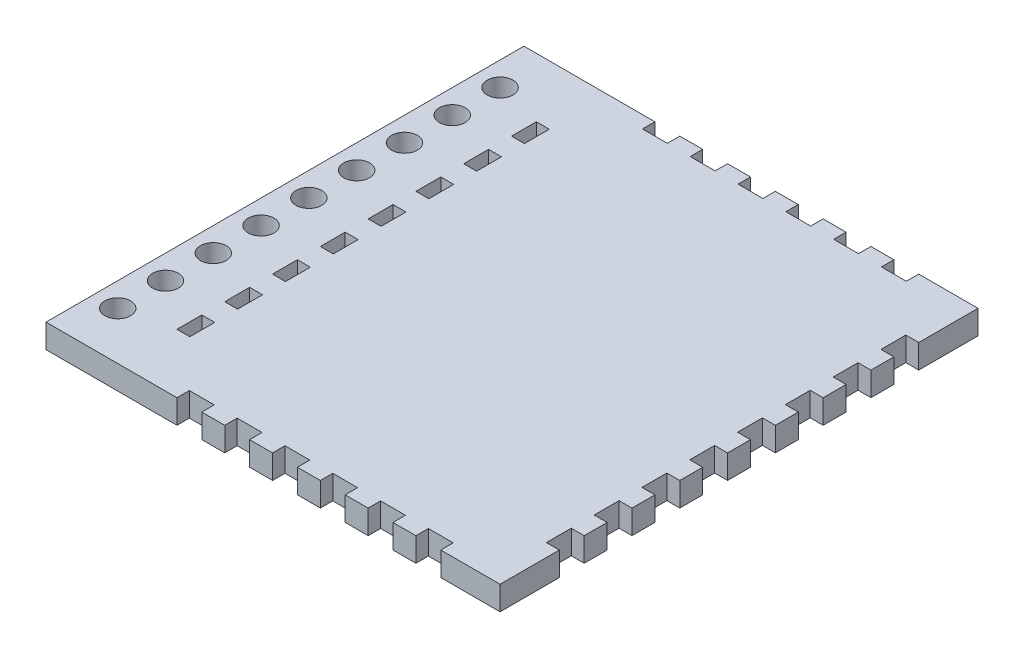
SolidWorks part; units mm, degrees
ref_plane "Front Plane" through (0, 0, 0) normal (0, 0, 1) x (1, 0, 0)
ref_plane "Top Plane" through (0, 0, 0) normal (0, 1, 0) x (1, 0, 0)
ref_plane "Right Plane" through (0, 0, 0) normal (1, 0, 0) x (0, 0, -1)
sketch "Sketch1" plane through (0, 0, 0) normal (0, 1, 0) x (1, 0, 0)
  line L1 (-50.8, -63.5) -> (50.8, -63.5)
  line L2 (-50.8, -63.5) -> (-50.8, 63.5)
  line L3 (-50.8, 63.5) -> (50.8, 63.5)
  line L4 (50.8, -63.5) -> (50.8, 63.5)
  line L5 (-50.8, -63.5) -> (50.8, 63.5) construction
  line L6 (-50.8, 63.5) -> (50.8, -63.5) construction
  line L11 (-41.275, -53.975) -> (41.275, 53.975) construction
  line L12 (-41.275, 53.975) -> (41.275, -53.975) construction
  point P0 (0, 0)
  point P5 (0, 0)
  dimension "D1" = 101.6
  dimension "D2" = 127
extrude "Boss-Extrude1" add sketch "Sketch1" along normal blind 6.35
sketch "Sketch2" plane through (0, 6.35, 0) normal (0, 1, 0) x (1, 0, 0)
  line L0 (-50.8, -63.5) -> (50.8, -63.5) construction
  line L1 (-35.052, -63.5) -> (-28.448, -63.5)
  line L2 (-35.052, -63.5) -> (-35.052, -60.198)
  line L3 (-35.052, -60.198) -> (-28.448, -60.198)
  line L4 (-28.448, -63.5) -> (-28.448, -60.198)
  line L5 (-22.352, -63.5) -> (-22.352, -60.198)
  line L6 (-22.352, -63.5) -> (-15.748, -63.5)
  line L7 (-15.748, -63.5) -> (-15.748, -60.198)
  line L8 (-22.352, -60.198) -> (-15.748, -60.198)
  line L9 (-9.652, -63.5) -> (-9.652, -60.198)
  line L10 (-9.652, -63.5) -> (-3.048, -63.5)
  line L11 (-3.048, -63.5) -> (-3.048, -60.198)
  line L12 (-9.652, -60.198) -> (-3.048, -60.198)
  line L13 (3.048, -63.5) -> (3.048, -60.198)
  line L14 (3.048, -63.5) -> (9.652, -63.5)
  line L15 (9.652, -63.5) -> (9.652, -60.198)
  line L16 (3.048, -60.198) -> (9.652, -60.198)
  line L17 (15.748, -63.5) -> (15.748, -60.198)
  line L18 (15.748, -63.5) -> (22.352, -63.5)
  line L19 (22.352, -63.5) -> (22.352, -60.198)
  line L20 (15.748, -60.198) -> (22.352, -60.198)
  line L21 (28.448, -63.5) -> (28.448, -60.198)
  line L22 (28.448, -63.5) -> (35.052, -63.5)
  line L23 (35.052, -63.5) -> (35.052, -60.198)
  line L24 (28.448, -60.198) -> (35.052, -60.198)
  line L25 (0, 0) -> (9.652, 0) construction
  line L26 (28.448, 60.198) -> (35.052, 60.198)
  line L27 (35.052, 63.5) -> (35.052, 60.198)
  line L28 (28.448, 63.5) -> (35.052, 63.5)
  line L29 (28.448, 63.5) -> (28.448, 60.198)
  line L30 (15.748, 60.198) -> (22.352, 60.198)
  line L31 (22.352, 63.5) -> (22.352, 60.198)
  line L32 (15.748, 63.5) -> (22.352, 63.5)
  line L33 (15.748, 63.5) -> (15.748, 60.198)
  line L34 (3.048, 60.198) -> (9.652, 60.198)
  line L35 (9.652, 63.5) -> (9.652, 60.198)
  line L36 (3.048, 63.5) -> (9.652, 63.5)
  line L37 (3.048, 63.5) -> (3.048, 60.198)
  line L38 (-9.652, 60.198) -> (-3.048, 60.198)
  line L39 (-3.048, 63.5) -> (-3.048, 60.198)
  line L40 (-9.652, 63.5) -> (-3.048, 63.5)
  line L41 (-9.652, 63.5) -> (-9.652, 60.198)
  line L42 (-22.352, 60.198) -> (-15.748, 60.198)
  line L43 (-15.748, 63.5) -> (-15.748, 60.198)
  line L44 (-22.352, 63.5) -> (-15.748, 63.5)
  line L45 (-22.352, 63.5) -> (-22.352, 60.198)
  line L46 (-28.448, 63.5) -> (-28.448, 60.198)
  line L47 (-35.052, 60.198) -> (-28.448, 60.198)
  line L48 (-35.052, 63.5) -> (-35.052, 60.198)
  line L49 (-35.052, 63.5) -> (-28.448, 63.5)
  line L50 (-50.8, 63.5) -> (-50.8, -63.5) construction
  line L51 (-50.8, 28.448) -> (-47.371, 28.448)
  line L52 (-50.8, 28.448) -> (-50.8, 35.052)
  line L53 (-50.8, 35.052) -> (-47.371, 35.052)
  line L54 (-47.371, 28.448) -> (-47.371, 35.052)
  line L55 (50.8, 63.5) -> (-50.8, 63.5) construction
  line L56 (-50.8, 15.748) -> (-47.371, 15.748)
  line L57 (-50.8, 15.748) -> (-50.8, 22.352)
  line L58 (-50.8, 22.352) -> (-47.371, 22.352)
  line L59 (-47.371, 15.748) -> (-47.371, 22.352)
  line L60 (-50.8, 3.048) -> (-47.371, 3.048)
  line L61 (-50.8, 3.048) -> (-50.8, 9.652)
  line L62 (-50.8, 9.652) -> (-47.371, 9.652)
  line L63 (-47.371, 3.048) -> (-47.371, 9.652)
  line L64 (-50.8, -9.652) -> (-47.371, -9.652)
  line L65 (-50.8, -9.652) -> (-50.8, -3.048)
  line L66 (-50.8, -3.048) -> (-47.371, -3.048)
  line L67 (-47.371, -9.652) -> (-47.371, -3.048)
  line L68 (-50.8, -22.352) -> (-47.371, -22.352)
  line L69 (-50.8, -22.352) -> (-50.8, -15.748)
  line L70 (-50.8, -15.748) -> (-47.371, -15.748)
  line L71 (-47.371, -22.352) -> (-47.371, -15.748)
  line L72 (-50.8, -35.052) -> (-47.371, -35.052)
  line L73 (-50.8, -35.052) -> (-50.8, -28.448)
  line L74 (-50.8, -28.448) -> (-47.371, -28.448)
  line L75 (-47.371, -35.052) -> (-47.371, -28.448)
  line L84 (0, 0) -> (0, 15.748) construction
  line L93 (47.371, -35.052) -> (47.371, -28.448)
  line L94 (50.8, -28.448) -> (47.371, -28.448)
  line L95 (50.8, -35.052) -> (50.8, -28.448)
  line L96 (50.8, -35.052) -> (47.371, -35.052)
  line L97 (47.371, -22.352) -> (47.371, -15.748)
  line L98 (50.8, -15.748) -> (47.371, -15.748)
  line L99 (50.8, -22.352) -> (50.8, -15.748)
  line L100 (50.8, -22.352) -> (47.371, -22.352)
  line L101 (47.371, -9.652) -> (47.371, -3.048)
  line L102 (50.8, -3.048) -> (47.371, -3.048)
  line L103 (50.8, -9.652) -> (50.8, -3.048)
  line L104 (50.8, -9.652) -> (47.371, -9.652)
  line L105 (47.371, 3.048) -> (47.371, 9.652)
  line L106 (50.8, 9.652) -> (47.371, 9.652)
  line L107 (50.8, 3.048) -> (50.8, 9.652)
  line L108 (50.8, 3.048) -> (47.371, 3.048)
  line L109 (47.371, 15.748) -> (47.371, 22.352)
  line L110 (50.8, 22.352) -> (47.371, 22.352)
  line L111 (50.8, 15.748) -> (50.8, 22.352)
  line L112 (50.8, 15.748) -> (47.371, 15.748)
  line L113 (47.371, 28.448) -> (47.371, 35.052)
  line L114 (50.8, 35.052) -> (47.371, 35.052)
  line L115 (50.8, 28.448) -> (50.8, 35.052)
  line L116 (50.8, 28.448) -> (47.371, 28.448)
  line L117 (-50.8, -47.752) -> (-47.371, -47.752) [skipped]
  line L118 (-50.8, -47.752) -> (-50.8, -41.148) [skipped]
  line L119 (-50.8, -41.148) -> (-47.371, -41.148) [skipped]
  line L120 (-47.371, -47.752) -> (-47.371, -41.148) [skipped]
  line L121 (-50.8, -60.452) -> (-47.371, -60.452) [skipped]
  line L122 (-50.8, -60.452) -> (-50.8, -53.848) [skipped]
  line L123 (-50.8, -53.848) -> (-47.371, -53.848) [skipped]
  line L124 (-47.371, -60.452) -> (-47.371, -53.848) [skipped]
  line L125 (-50.8, 41.148) -> (-47.371, 41.148)
  line L126 (-50.8, 41.148) -> (-50.8, 47.752)
  line L127 (-50.8, 47.752) -> (-47.371, 47.752)
  line L128 (-47.371, 41.148) -> (-47.371, 47.752)
  line L129 (-50.8, -47.752) -> (-47.371, -47.752)
  line L130 (-50.8, -47.752) -> (-50.8, -41.148)
  line L131 (-50.8, -41.148) -> (-47.371, -41.148)
  line L132 (-47.371, -47.752) -> (-47.371, -41.148)
  line L133 (47.371, -47.752) -> (47.371, -41.148)
  line L134 (50.8, -41.148) -> (47.371, -41.148)
  line L135 (50.8, -47.752) -> (50.8, -41.148)
  line L136 (50.8, -47.752) -> (47.371, -47.752)
  line L137 (47.371, 41.148) -> (47.371, 47.752)
  line L138 (50.8, 47.752) -> (47.371, 47.752)
  line L139 (50.8, 41.148) -> (50.8, 47.752)
  line L140 (50.8, 41.148) -> (47.371, 41.148)
  point P6 (-31.75, -63.5)
  point P65 (-50.8, 31.75)
  dimension "D1" = 6.604
  dimension "D2" = 3.302
  dimension "D3" = 19.05
  dimension "D5" = 2
  dimension "D6" = 31.75
  dimension "D8" = 12.7
  dimension "D9" = 2
  dimension "D10" = 6.604
  dimension "D4" = 6
  dimension "D7" = 8
  dimension "D11" = 2
  dimension "D12" = 2
extrude "Cut-Extrude1" cut sketch "Sketch2" against normal through all
sketch "Sketch3" plane through (0, 6.35, 0) normal (0, 1, 0) x (1, 0, 0)
  line L1 (-50.8, 63.5) -> (-114.3, 63.5)
  line L2 (-50.8, 63.5) -> (-50.8, -63.5)
  line L3 (-50.8, -63.5) -> (-114.3, -63.5)
  line L4 (-114.3, 63.5) -> (-114.3, -63.5)
  line L5 (-50.8, -63.5) -> (-35.052, -63.5) construction
  circle A0 centre (-101.6, 50.8) radius 3.429
  circle A1 centre (-88.9, 50.8) radius 3.429
  circle A2 centre (-88.9, 38.1) radius 3.429
  circle A6 centre (-101.6, 38.1) radius 3.429
  circle A10 centre (-101.6, 25.4) radius 3.429
  circle A11 centre (-88.9, 25.4) radius 3.429
  circle A12 centre (-76.2, 50.8) radius 3.429
  circle A13 centre (-63.5, 50.8) radius 3.429
  circle A14 centre (-76.2, 38.1) radius 3.429
  circle A15 centre (-63.5, 38.1) radius 3.429
  circle A16 centre (-76.2, 25.4) radius 3.429
  circle A17 centre (-63.5, 25.4) radius 3.429
  circle A18 centre (-101.6, 12.7) radius 3.429
  circle A19 centre (-88.9, 12.7) radius 3.429
  circle A20 centre (-76.2, 12.7) radius 3.429
  circle A21 centre (-63.5, 12.7) radius 3.429
  circle A22 centre (-101.6, 0) radius 3.429
  circle A23 centre (-88.9, 0) radius 3.429
  circle A24 centre (-76.2, 0) radius 3.429
  circle A25 centre (-63.5, 0) radius 3.429
  circle A26 centre (-101.6, -12.7) radius 3.429
  circle A27 centre (-88.9, -12.7) radius 3.429
  circle A28 centre (-76.2, -12.7) radius 3.429
  circle A29 centre (-63.5, -12.7) radius 3.429
  circle A30 centre (-101.6, -25.4) radius 3.429
  circle A31 centre (-88.9, -25.4) radius 3.429
  circle A32 centre (-76.2, -25.4) radius 3.429
  circle A33 centre (-63.5, -25.4) radius 3.429
  circle A34 centre (-101.6, -38.1) radius 3.429
  circle A35 centre (-88.9, -38.1) radius 3.429
  circle A36 centre (-76.2, -38.1) radius 3.429
  circle A37 centre (-63.5, -38.1) radius 3.429
  circle A38 centre (-101.6, -50.8) radius 3.429
  circle A39 centre (-88.9, -50.8) radius 3.429
  circle A40 centre (-76.2, -50.8) radius 3.429
  circle A41 centre (-63.5, -50.8) radius 3.429
  dimension "D2" = 6.858
  dimension "D4" = 12.7
  dimension "D1" = 63.5
  dimension "D3" = 38.1
  dimension "D7" = 12.7
  dimension "D8" = 12.7
  dimension "D5" = 4
  dimension "D6" = 9
extrude "Boss-Extrude2" add sketch "Sketch3" against normal blind 6.35
sketch "Sketch4" plane through (0, 6.35, 0) normal (0, 1, 0) x (1, 0, 0)
  line L0 (-114.3, -63.5) -> (-35.052, -63.5) construction
  line L1 (-69.85, -63.5) -> (-114.3, -63.5)
  line L2 (-69.85, -63.5) -> (-69.85, 63.5)
  line L3 (-69.85, 63.5) -> (-114.3, 63.5)
  line L4 (-114.3, -63.5) -> (-114.3, 63.5)
  point P5 (-69.0189, -63.5)
  dimension "D1" = 44.45
extrude "Cut-Extrude2" cut sketch "Sketch4" against normal through all
